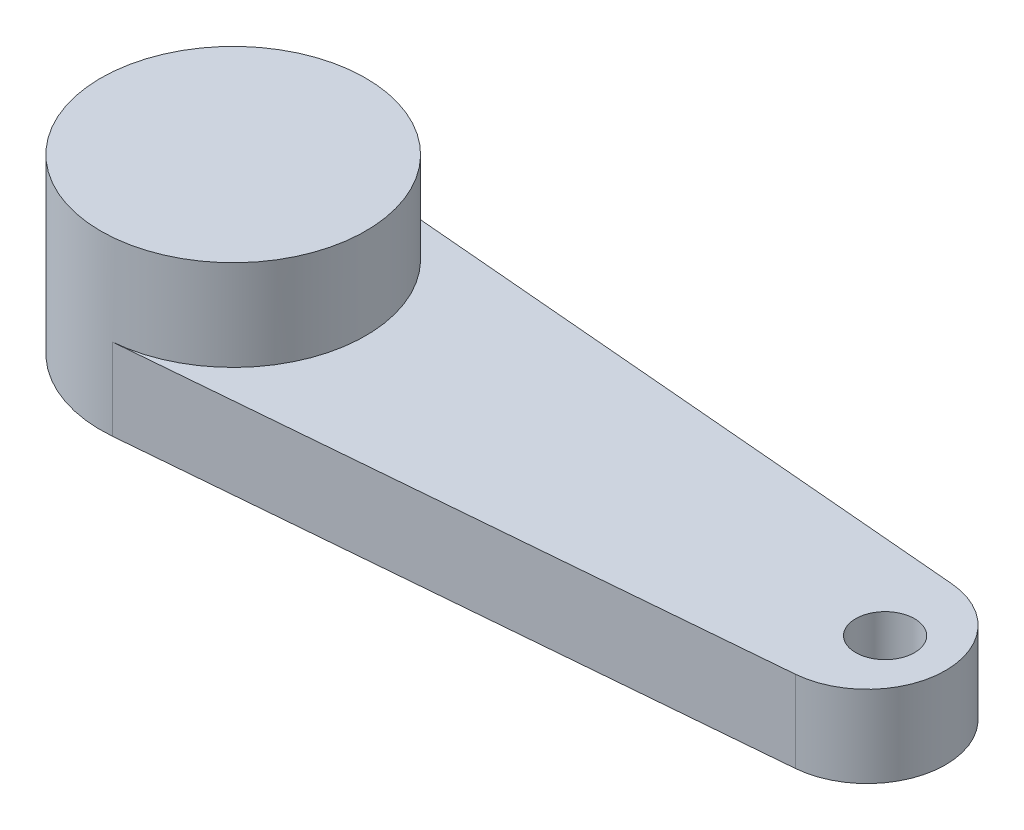
SolidWorks part; units mm, degrees
ref_plane "Front Plane" through (0, 0, 0) normal (0, 0, 1) x (1, 0, 0)
ref_plane "Top Plane" through (0, 0, 0) normal (0, 1, 0) x (1, 0, 0)
ref_plane "Right Plane" through (0, 0, 0) normal (1, 0, 0) x (0, 0, -1)
sketch "Sketch1" plane through (0, 0, 0) normal (0, 1, 0) x (1, 0, 0)
  line L0 (0, 0) -> (3.375, 0)
  line L1 (0.2874, 3.3627) -> (16.3153, 1.9927)
  line L2 (16.3153, -1.9927) -> (0.2874, -3.3627)
  line L3 (3.375, 0) -> (14.145, 0) construction
  line L4 (14.145, 0) -> (18.145, 0) construction
  arc A0 (0.2874, 3.3627) -> (0.2874, -3.3627) centre (0, 0) ccw
  arc A2 (16.3153, -1.9927) -> (16.3153, 1.9927) centre (16.145, 0) ccw
  arc A3 (3.375, 0) -> (0.2874, 3.3627) centre (0, 0) ccw construction
  arc A4 (0.2874, -3.3627) -> (3.375, 0) centre (0, 0) ccw construction
  arc A5 (14.145, 0) -> (16.3153, -1.9927) centre (16.145, 0) ccw construction
  arc A6 (16.3153, 1.9927) -> (14.145, 0) centre (16.145, 0) ccw construction
  circle A7 centre (16.605, 0) radius 0.75
  point P3 (-3.375, 0)
  point P6 (18.145, 0)
  point P8 (18.145, 0)
  point P10 (17.355, 0)
  dimension "D1" = 6.75
  dimension "D2" = 21.52
  dimension "D3" = 4
  dimension "D4" = 1.5
  dimension "D5" = 0.79
extrude "Boss-Extrude1" add sketch "Sketch1" along normal blind 2.08
sketch "Sketch2" plane through (0, 2.08, 0) normal (0, 1, 0) x (1, 0, 0)
  circle A0 centre (0, 0) radius 3.375
  arc A1 (0.2874, 3.3627) -> (0.2874, -3.3627) centre (0, 0) ccw construction
  arc A2 (0.2874, 3.3627) -> (0.2874, -3.3627) centre (0, 0) ccw construction
extrude "Boss-Extrude2" add sketch "Sketch2" along normal blind 2.31
sketch "Sketch3" plane through (0, 0, 0) normal (0, 1, 0) x (1, 0, 0)
  circle A0 centre (0, 0) radius 2.25
  dimension "D1" = 4.5
extrude "Cut-Extrude1" cut sketch "Sketch3" along normal blind 0.84
sketch "Moving attachment profile sketch" plane through (0, 0, 0) normal (0, 0, 1) x (1, 0, 0)
  line L2 (15.405, 2.08) -> (13.905, 2.08) construction
  line L3 (13.905, 0) -> (15.405, 0) construction
  line L4 (14.655, 2.08) -> (14.655, 0) construction
  point P6 (14.655, 1.04)
